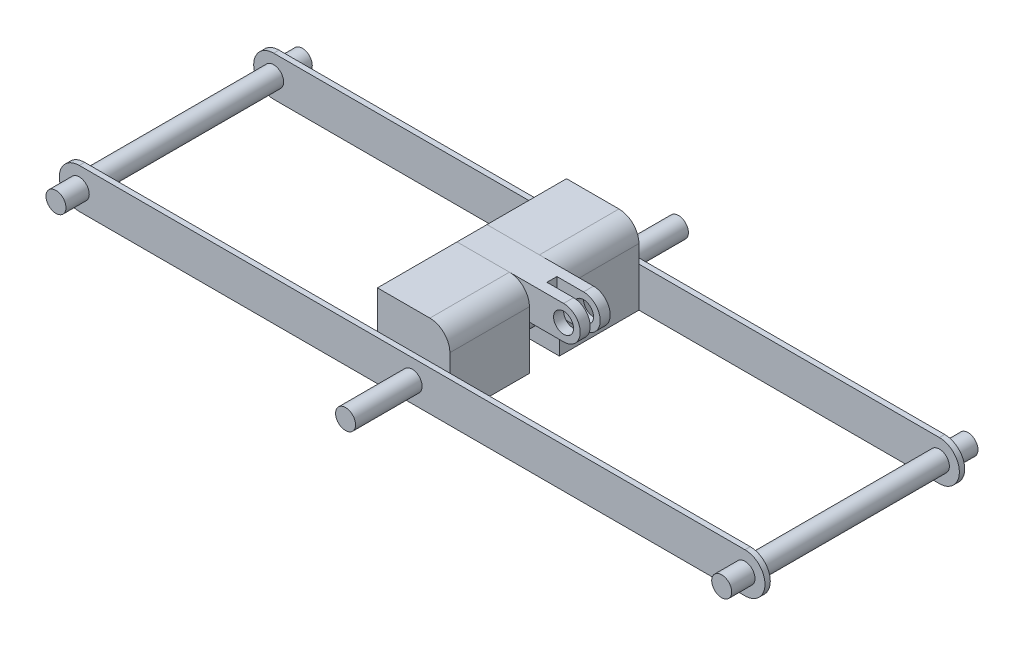
SolidWorks part; units mm, degrees
ref_plane "前视" through (0, 0, 0) normal (0, 0, 1) x (1, 0, 0)
ref_plane "上视" through (0, 0, 0) normal (0, 1, 0) x (1, 0, 0)
ref_plane "右视" through (0, 0, 0) normal (1, 0, 0) x (0, 0, -1)
sketch "草图1" plane through (0, 0, 0) normal (0, 0, 1) x (1, 0, 0)
  line L0 (0, 23.9167) -> (0, -26.1144) construction
  line L1 (-34.779, 0) -> (35.8075, 0) construction
  circle A0 centre (0, 0) radius 15
  circle A1 centre (1000, 0) radius 15
  dimension "D1" = 30
  dimension "D3" = 1000
  dimension "D2" = 2
extrude "凸台-拉伸1" add sketch "草图1" along normal mid plane 370
ref_plane "基准面1" through (0, 0, 150) normal (0, 0, 1) x (1, 0, 0)
ref_point "点1"
sketch "草图2" plane through (0, 0, 150) normal (0, 0, 1) x (1, 0, 0)
  line L0 (0, 30) -> (1000, 30)
  line L1 (1000, -30) -> (0, -30)
  arc A0 (0, 30) -> (0, -30) centre (0, 0) ccw
  arc A1 (1000, -30) -> (1000, 30) centre (1000, 0) ccw
  dimension "D1" = 60
  dimension "D2" = 60
extrude "凸台-拉伸2" add sketch "草图2" against normal blind 8 separate body
mirror "镜向1" about plane through (0, 0, 0) normal (0, 0, 1) of bodies 103
sketch "草图3" plane through (0, 0, 0) normal (0, 0, 1) x (1, 0, 0)
  circle A0 centre (500, 0) radius 15
  dimension "D1" = 30
  dimension "D2" = 500
extrude "凸台-拉伸3" add sketch "草图3" along normal mid plane 500
sketch "草图5" plane through (0, 0, 0) normal (0, 0, 1) x (1, 0, 0)
  line L0 (600, 86.6939) -> (439.9208, 86.6939)
  line L1 (439.9208, 86.6939) -> (439.9208, 36.6939)
  line L2 (439.9208, 36.6939) -> (600, 36.6939)
  circle A0 centre (600, 61.6939) radius 15
  arc A1 (600, 36.6939) -> (600, 86.6939) centre (600, 61.6939) ccw
  dimension "D1" = 30
  dimension "D2" = 50
  dimension "D3" = 600
extrude "凸台-拉伸4" add sketch "草图5" along normal mid plane 45 separate body
sketch "草图6" plane through (0, 0, -142) normal (0, 0, 1) x (1, 0, 0)
  line L0 (439.9208, -30) -> (439.9208, 86.6939)
  line L1 (0, -30) -> (1000, -30) construction
  line L2 (439.9208, 86.6939) -> (548.6715, 86.6939)
  line L3 (600, 86.6939) -> (439.9208, 86.6939) construction
  line L4 (548.6715, 86.6939) -> (548.6715, -30)
  line L5 (548.6715, -30) -> (439.9208, -30)
extrude "凸台-拉伸5" add sketch "草图6" along normal up to surface (119.5 mm away) separate body up to face at (526.2104, 61.6939, -22.5)
mirror "镜向2" about plane through (0, 0, 0) normal (0, 0, 1) of bodies 109
fillet "圆角1" radius 30 1 edges at (548.6715, 86.6939, -82.25)
fillet "圆角2" radius 30 1 edges at (548.6715, 86.6939, 82.25)
sketch "草图9" plane through (0, 0, 0) normal (0, 0, 1) x (1, 0, 0)
  line L0 (600, 86.6939) -> (630.2582, 86.6939)
  line L1 (600, 86.6939) -> (439.9208, 86.6939) construction
  line L2 (630.2582, 86.6939) -> (630.2582, 36.6939)
  line L3 (439.9208, 36.6939) -> (600, 36.6939) construction
  line L4 (630.2582, 36.6939) -> (600, 36.6939)
  line L5 (600, 86.6939) -> (559.9905, 86.6939)
  line L6 (559.9905, 86.6939) -> (559.9905, 36.6939)
  line L7 (559.9905, 36.6939) -> (600, 36.6939)
extrude "切除-拉伸2" cut sketch "草图9" against normal mid plane 15
scale "缩放比例1" bodies to scale 101 102 107 109 110 111 scale about origin uniform scaling yes scale factor 0.6
